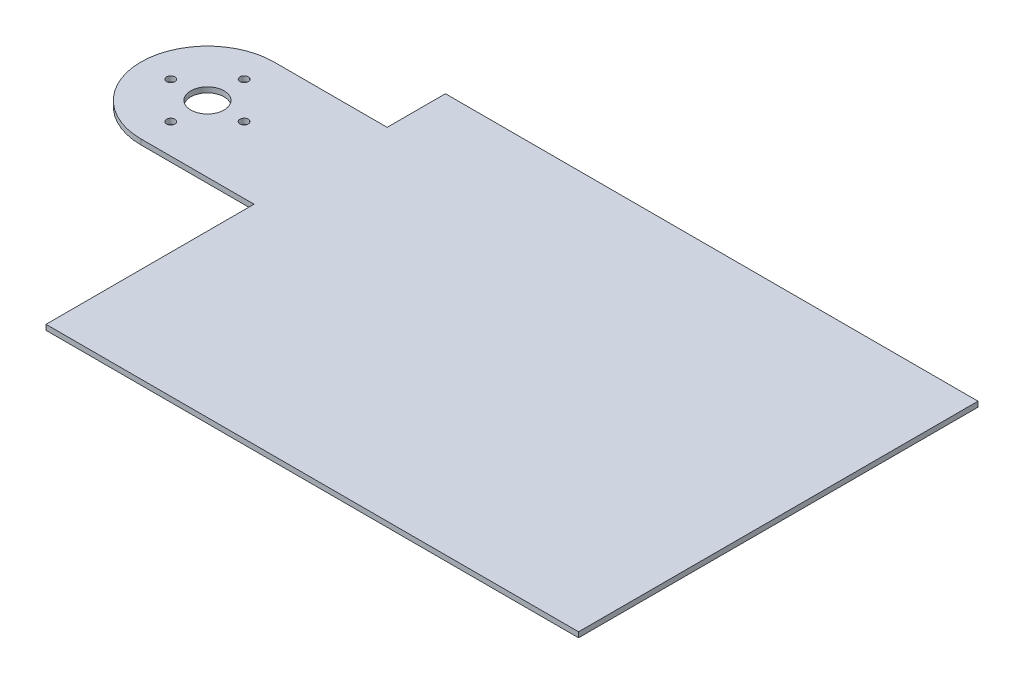
SolidWorks part; units mm, degrees
ref_plane "Front Plane" through (0, 0, 0) normal (0, 0, 1) x (1, 0, 0)
ref_plane "Top Plane" through (0, 0, 0) normal (0, 1, 0) x (1, 0, 0)
ref_plane "Right Plane" through (0, 0, 0) normal (1, 0, 0) x (0, 0, -1)
sketch "Sketch1" plane through (0, 0, 0) normal (0, 1, 0) x (1, 0, 0)
  line L0 (0, 12.7) -> (21.59, 12.7)
  line L2 (21.59, -12.7) -> (0, -12.7)
  line L3 (21.59, 12.7) -> (21.59, 23.8125)
  line L4 (21.59, -52.3875) -> (123.19, -52.3875)
  line L5 (21.59, -52.3875) -> (21.59, -12.7)
  line L6 (21.59, 23.8125) -> (123.19, 23.8125)
  line L7 (123.19, -52.3875) -> (123.19, 23.8125)
  arc A0 (0, 12.7) -> (0, -12.7) centre (0, 0) ccw
  circle A1 centre (7, 0) radius 0.8
  circle A2 centre (0, -7) radius 0.8
  circle A3 centre (-7, 0) radius 0.8
  circle A4 centre (0, 7) radius 0.8
  circle A5 centre (0, 0) radius 3.175
  point P21 (0, 0)
  dimension "D1" = 12.7
  dimension "D3" = 1.6
  dimension "D9" = 6.35
  dimension "D2" = 7
  dimension "D5" = 21.59
  dimension "D6" = 101.6
  dimension "D7" = 76.2
  dimension "D8" = 23.8125
  dimension "D4" = 4
extrude "Boss-Extrude1" add sketch "Sketch1" along normal mid plane 1
equation "\"D2@Sketch1\"=7mm"
equation "\"D3@Sketch1\"=1.6mm"
equation "\"D1@Boss-Extrude1\"=1mm"
